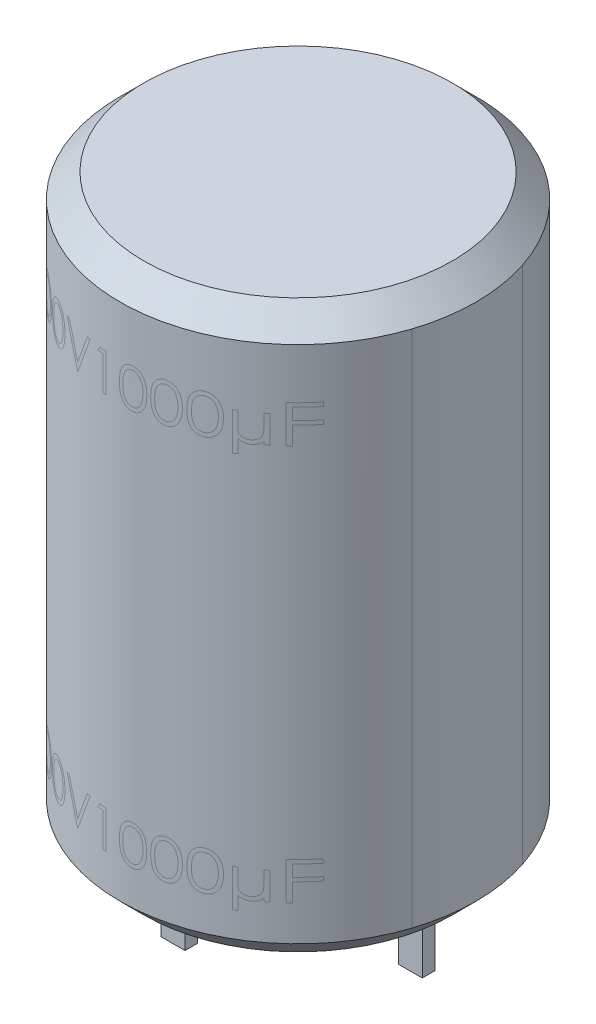
SolidWorks part; units mm, degrees
ref_plane "Alzado" through (0, 0, 0) normal (0, 0, 1) x (1, 0, 0)
ref_plane "Planta" through (0, 0, 0) normal (0, 1, 0) x (1, 0, 0)
ref_plane "Vista lateral" through (0, 0, 0) normal (1, 0, 0) x (0, 0, -1)
sketch "Croquis1" plane through (0, 0, 0) normal (0, 1, 0) x (1, 0, 0)
  circle A0 centre (0, 0) radius 11.25
  dimension "D1" = 22.5
extrude "Saliente-Extruir1" add sketch "Croquis1" along normal blind 35.8
chamfer "Chaflán1" distance 1.5 angle 45 2 edges at (0, 0, 11.25) (0, 35.8, 11.25)
sketch "Croquis3" plane through (0, 0, 0) normal (0, -1, 0) x (1, 0, 0)
  line L0 (0, 0) -> (0, 9.75) construction
  line L9 (0, 0) -> (-9.75, 0) construction
  line L10 (-5.25, 3.4) -> (-3.75, 3.4)
  line L11 (-5.25, 3.4) -> (-5.25, 2.6)
  line L12 (-5.25, 2.6) -> (-3.75, 2.6)
  line L13 (-3.75, 3.4) -> (-3.75, 2.6)
  line L15 (3.75, -2.6) -> (5.25, -2.6)
  line L16 (3.75, -2.6) -> (3.75, -3.4)
  line L17 (3.75, -3.4) -> (5.25, -3.4)
  line L18 (5.25, -2.6) -> (5.25, -3.4)
  circle A0 centre (0, 0) radius 9.75 construction
  point P4 (-4.5, 2.6)
  point P15 (4.5, -3.4)
  point P16 (5.25, -3)
  point P17 (-5.25, 3)
  dimension "D1" = 1.5
  dimension "D2" = 0.8
  dimension "D3" = 9
  dimension "D4" = 6
  dimension "D5" = 9
  dimension "D6" = 6
extrude "Saliente-Extruir2" add sketch "Croquis3" along normal blind 7
sketch "Croquis4" plane through (0, 0, 0) normal (1, 0, 0) x (0, 0, -1)
  line L0 (9.75, 35.8) -> (-9.75, 35.8) construction
  line L1 (-3.5, 35.8) -> (3.5, 35.8)
  line L2 (-3.5, 35.8) -> (-3.5, 0)
  line L3 (-3.5, 0) -> (3.5, 0)
  line L4 (3.5, 35.8) -> (3.5, 0)
  line L5 (-9.75, 0) -> (9.75, 0) construction
  point P8 (0, 35.8)
  dimension "D1" = 7
split line "Línea de partición1"
sketch "Croquis5" plane through (0, 0, 0) normal (0, 0, 1) x (1, 0, 0)
  line L0 (-9.75, 28.7358) -> (9.75, 28.7358) construction
  line L1 (-9.75, 3.7358) -> (9.75, 3.7358) construction
  text T0 "100V1000µF" font "Century Gothic" height in points 9
  text T1 "100V1000µF" font "Century Gothic" height in points 9
  dimension "D1" = 2
split line "Línea de partición2"
